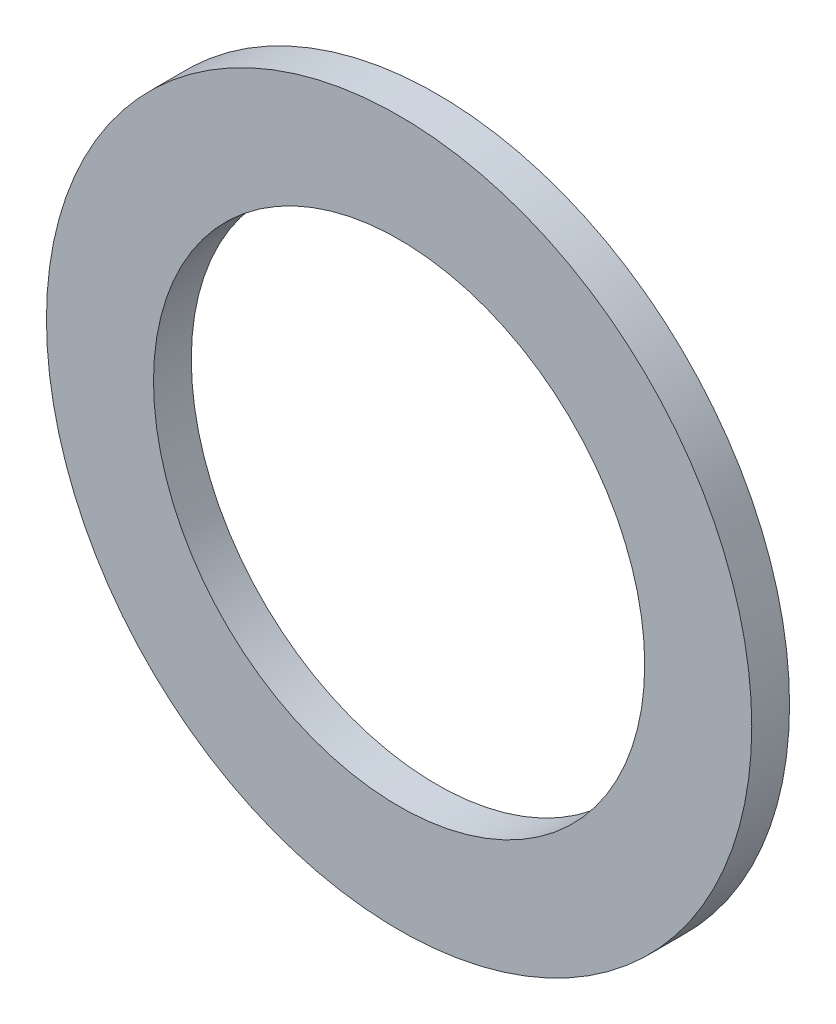
SolidWorks part; units mm, degrees
ref_plane "Спереди" through (0, 0, 0) normal (0, 0, 1) x (1, 0, 0)
ref_plane "Сверху" through (0, 0, 0) normal (0, 1, 0) x (1, 0, 0)
ref_plane "Справа" through (0, 0, 0) normal (1, 0, 0) x (0, 0, -1)
sketch "Эскиз1" plane through (0, 0, 0) normal (0, 0, 1) x (1, 0, 0)
  circle A0 centre (0, 0) radius 14
  circle A1 centre (0, 0) radius 9.75
  dimension "D1" = 19.5
  dimension "D2" = 28
extrude "Вытянуть1" add sketch "Эскиз1" along normal blind 1.5
